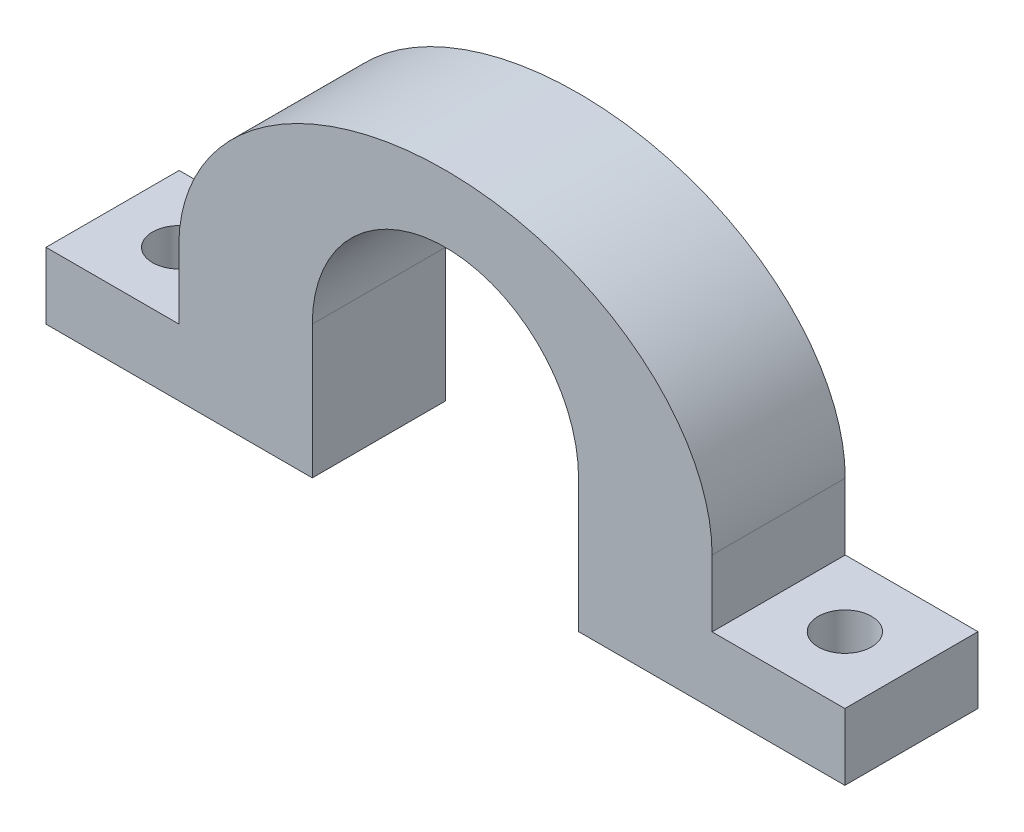
SolidWorks part; units mm, degrees
material "Acrylic (Medium-high impact)"
ref_plane "Front Plane" through (0, 0, 0) normal (0, 0, 1) x (1, 0, 0)
ref_plane "Top Plane" through (0, 0, 0) normal (0, 1, 0) x (1, 0, 0)
ref_plane "Right Plane" through (0, 0, 0) normal (1, 0, 0) x (0, 0, -1)
sketch "Sketch1" plane through (0, 0, 0) normal (0, 0, 1) x (1, 0, 0)
  line L0 (-30, -10) -> (-30, -5)
  line L1 (30, -5) -> (30, -10)
  line L2 (10, 0) -> (10, -10)
  line L3 (-30, -5) -> (-20, -5)
  line L4 (30, -5) -> (20.0292, -5)
  line L5 (-20, -5) -> (-20, 0)
  line L6 (20.0292, -5) -> (20.0292, 0)
  line L15 (0, -10) -> (30, -10)
  line L16 (30, -10) -> (-30, -10)
  line L17 (-10, 0) -> (-10, -10)
  circle A0 centre (0, 0) radius 10
  ellipse E0 centre (0, 0) end of major axis (20.0292, 0) minor radius 15.0219
  point P5 (0, 15)
  point P12 (0, 12.607)
  dimension "D3" = 15
extrude "Boss-Extrude1" add sketch "Sketch1" along normal blind 10
sketch "Sketch2" plane through (0, -5, 0) normal (0, 1, 0) x (1, 0, 0)
  line L0 (-30, 0) -> (-20, 0) construction
  line L1 (-30, -10) -> (-30, 0) construction
  line L2 (30, -10) -> (30, 0) construction
  circle A0 centre (-25, -5) radius 2
  circle A1 centre (25, -5) radius 2
  dimension "D1" = 5
  dimension "D3" = 5
  dimension "D2" = 5
extrude "Cut-Extrude1" cut sketch "Sketch2" against normal through all
